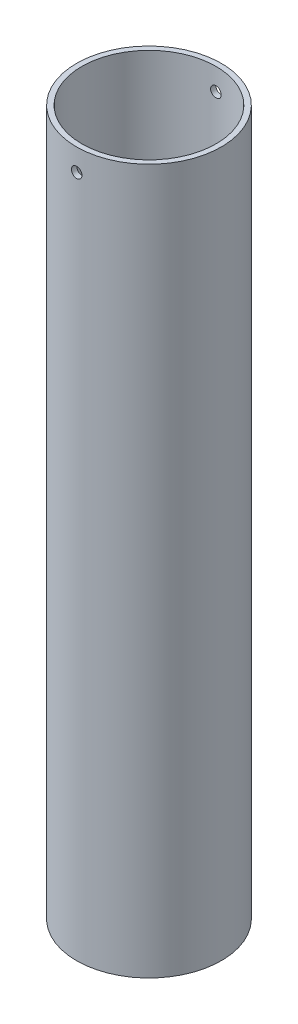
SolidWorks part; units mm, degrees
ref_plane "Front Plane" through (0, 0, 0) normal (0, 0, 1) x (1, 0, 0)
ref_plane "Top Plane" through (0, 0, 0) normal (0, 1, 0) x (1, 0, 0)
ref_plane "Right Plane" through (0, 0, 0) normal (1, 0, 0) x (0, 0, -1)
sketch "Sketch2" plane through (0, 0, 0) normal (0, 1, 0) x (1, 0, 0)
  circle A0 centre (0, 0) radius 38.1
  circle A1 centre (0, 0) radius 41.1
  dimension "D1" = 76.2
  dimension "D2" = 3
extrude "Boss-Extrude1" add sketch "Sketch2" along normal mid plane 400
sketch "Sketch4" plane through (0, 0, 0) normal (0, 0, 1) x (1, 0, 0)
  line L0 (0, 200) -> (0, 187.5) construction
  line L1 (41.1, 200) -> (-41.1, 200) construction
  circle A0 centre (0, 187.5) radius 3
  dimension "D2" = 6
  dimension "D1" = 12.5
extrude "Cut-Extrude1" cut sketch "Sketch4" against normal through all both and the other way through all
ref_plane "Plane1" through (0, 100, 0) normal (0, 1, 0) x (1, 0, 0)
